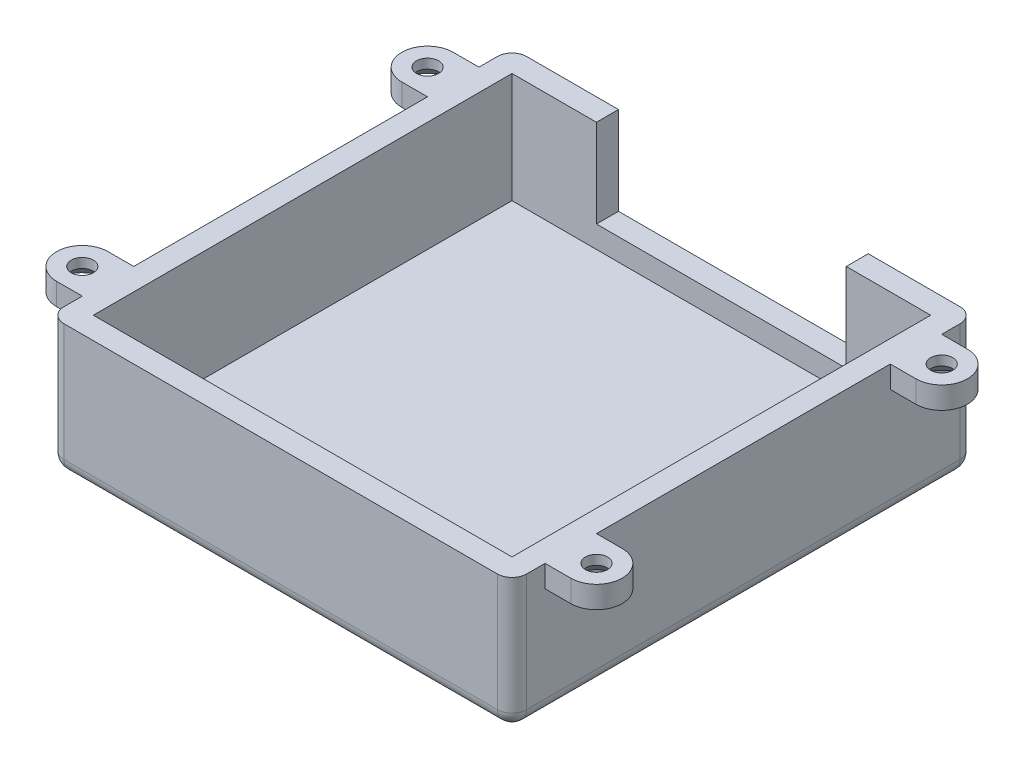
SolidWorks part; units mm, degrees
material "PLA Infill"
ref_plane "Front Plane" through (0, 0, 0) normal (0, 0, 1) x (1, 0, 0)
ref_plane "Top Plane" through (0, 0, 0) normal (0, 1, 0) x (1, 0, 0)
ref_plane "Right Plane" through (0, 0, 0) normal (1, 0, 0) x (0, 0, -1)
sketch "Sketch1" plane through (0, 0, 0) normal (0, 1, 0) x (1, 0, 0)
  line L16 (0, 0) -> (63, 0)
  line L17 (0, 0) -> (0, 63)
  line L18 (0, 63) -> (63, 63)
  line L19 (63, 0) -> (63, 63)
  dimension "D1" = 63
  dimension "D2" = 63
extrude "Boss-Extrude1" add sketch "Sketch1" along normal blind 18
shell "Shell2" thickness 3
sketch "Sketch2" plane through (0, 0, -63) normal (0, 0, -1) x (-1, 0, 0)
  line L0 (-48.5, 18) -> (-14.5, 18)
  line L1 (-48.5, 6) -> (-14.5, 6)
  line L2 (-48.5, 6) -> (-48.5, 18)
  line L4 (-14.5, 6) -> (-14.5, 18)
  line L5 (-63, 18) -> (0, 18) construction
  line L6 (-31.5, 0) -> (-31.5, 18) construction
  line L7 (-63, 0) -> (0, 0) construction
  point P8 (-31.5, 18)
  dimension "D1" = 12
  dimension "D2" = 34
extrude "Cut-Extrude1" cut sketch "Sketch2" against normal up to surface (3 mm away) up to face at (31.5, 10.5, -60)
fillet "Fillet2" radius 2 8 edges at (31.5, 0, 0) (63, 0, -31.5) (31.5, 0, -63) (0, 0, -31.5) (63, 9, 0) (0, 9, 0) (0, 9, -63) (63, 9, -63)
sketch "Sketch4" plane through (0, 18, 0) normal (0, 1, 0) x (1, 0, 0)
  line L0 (31.5, -1000) -> (31.5, 49000) construction
  line L1 (2, 0) -> (61, 0) construction
  line L7 (-7, 55) -> (0, 55) construction
  line L8 (0, 58.5) -> (-7, 58.5) construction
  line L9 (0, 58.5) -> (0, 51.5)
  line L10 (0, 51.5) -> (-7, 51.5) construction
  line L11 (-7, 58.5) -> (-7, 51.5) construction
  line L12 (-3.5, 58.5) -> (0, 58.5)
  line L13 (-3.5, 51.5) -> (0, 51.5)
  line L14 (-1000, 31.5) -> (49000, 31.5) construction
  line L24 (0, 61) -> (0, 2) construction
  line L25 (70, 58.5) -> (70, 51.5) construction
  line L26 (63, 51.5) -> (70, 51.5) construction
  line L27 (63, 58.5) -> (70, 58.5) construction
  line L28 (70, 55) -> (63, 55) construction
  line L29 (66.5, 51.5) -> (63, 51.5)
  line L30 (66.5, 58.5) -> (63, 58.5)
  line L31 (63, 58.5) -> (63, 51.5)
  line L32 (70, 8) -> (63, 8) construction
  line L33 (63, 4.5) -> (70, 4.5) construction
  line L34 (63, 11.5) -> (70, 11.5) construction
  line L35 (70, 4.5) -> (70, 11.5) construction
  line L36 (-7, 4.5) -> (-7, 11.5) construction
  line L37 (0, 11.5) -> (-7, 11.5) construction
  line L38 (0, 4.5) -> (-7, 4.5) construction
  line L39 (-7, 8) -> (0, 8) construction
  line L40 (63, 4.5) -> (63, 11.5)
  line L41 (66.5, 4.5) -> (63, 4.5)
  line L42 (66.5, 11.5) -> (63, 11.5)
  line L43 (-3.5, 11.5) -> (0, 11.5)
  line L44 (-3.5, 4.5) -> (0, 4.5)
  line L45 (0, 4.5) -> (0, 11.5)
  circle A0 centre (-3.5, 55) radius 1.5
  arc A1 (-3.5, 51.5) -> (-3.5, 58.5) centre (-3.5, 55) cw
  arc A8 (66.5, 51.5) -> (66.5, 58.5) centre (66.5, 55) ccw
  circle A9 centre (66.5, 55) radius 1.5
  circle A10 centre (66.5, 8) radius 1.5
  arc A11 (66.5, 11.5) -> (66.5, 4.5) centre (66.5, 8) cw
  arc A12 (-3.5, 11.5) -> (-3.5, 4.5) centre (-3.5, 8) ccw
  circle A13 centre (-3.5, 8) radius 1.5
  point P5 (31.5, 0)
  point P6 (0, 0)
  point P8 (0, 0)
  point P20 (0, 0)
  point P22 (0, 0)
  point P24 (0, 0)
  point P25 (0, 0)
  point P26 (-0.8628, 51.2422)
  point P42 (0, 31.5)
  dimension "D1" = 3
  dimension "D2" = 7
  dimension "D3" = 55
  dimension "D4" = 3.5
extrude "Boss-Extrude2" add sketch "Sketch4" against normal blind 3
chamfer "Chamfer1" distance 1.7 angle 45 4 edges at (-3.5, 15, -53.5) (66.5, 15, -6.5) (-3.5, 15, -9.5) (66.5, 15, -56.5)
